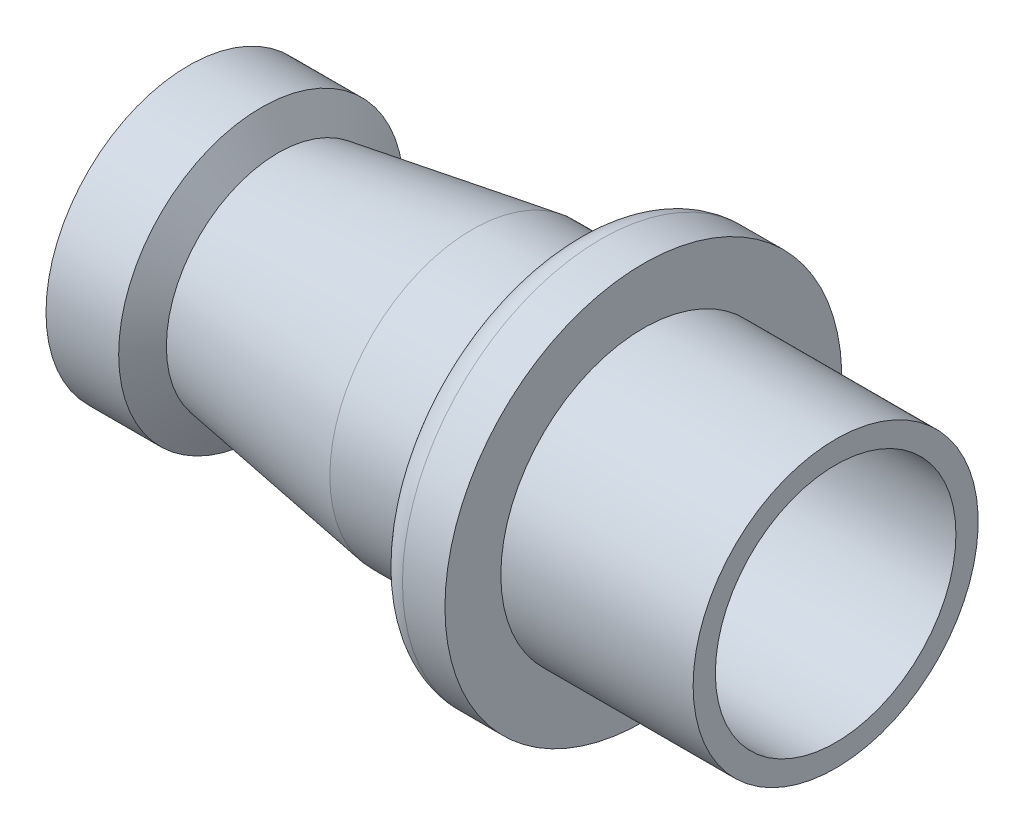
SolidWorks part; units mm, degrees
ref_plane "Front Plane" through (0, 0, 0) normal (0, 0, 1) x (1, 0, 0)
ref_plane "Top Plane" through (0, 0, 0) normal (0, 1, 0) x (1, 0, 0)
ref_plane "Right Plane" through (0, 0, 0) normal (1, 0, 0) x (0, 0, -1)
sketch "Sketch1" plane through (0, 0, 0) normal (0, 0, 1) x (1, 0, 0)
  line L0 (82.8943, 146.2953) -> (90.2545, 146.2953) construction
  line L1 (88.4765, 146.943) -> (88.8982, 146.943)
  line L2 (88.4765, 146.943) -> (88.4765, 147.7198) construction
  line L3 (88.9617, 147.197) -> (89.2538, 147.197)
  line L4 (87.1869, 146.943) -> (87.1869, 146.715)
  line L5 (89.302, 146.943) -> (89.302, 146.2953) construction
  line L6 (87.5171, 146.943) -> (87.5942, 146.8033)
  line L7 (87.1869, 146.943) -> (87.5171, 146.943)
  line L8 (88.4765, 146.943) -> (87.5942, 146.8033)
  line L9 (87.5942, 146.8033) -> (87.5942, 146.2953) construction
  line L10 (88.4765, 147.7198) -> (88.8982, 147.7198) construction
  line L11 (88.6289, 146.715) -> (87.1869, 146.715)
  line L12 (88.8982, 147.7198) -> (88.8982, 146.774) construction
  line L13 (89.2538, 147.197) -> (89.2538, 146.943)
  line L14 (90.1275, 146.943) -> (90.1275, 146.842)
  line L15 (90.1275, 146.842) -> (88.6289, 146.842)
  line L16 (88.6289, 146.842) -> (88.6289, 146.715)
  line L18 (89.2538, 146.943) -> (90.1275, 146.943)
  line L22 (88.8982, 146.943) -> (88.9617, 147.197)
  dimension "D1" = 188.997
revolve "Revolve1" add sketch "Sketch1" angle 360 about L0
fillet "Fillet2" radius 0.127 1 edges at (88.9617, 146.2953, 0.9017)
